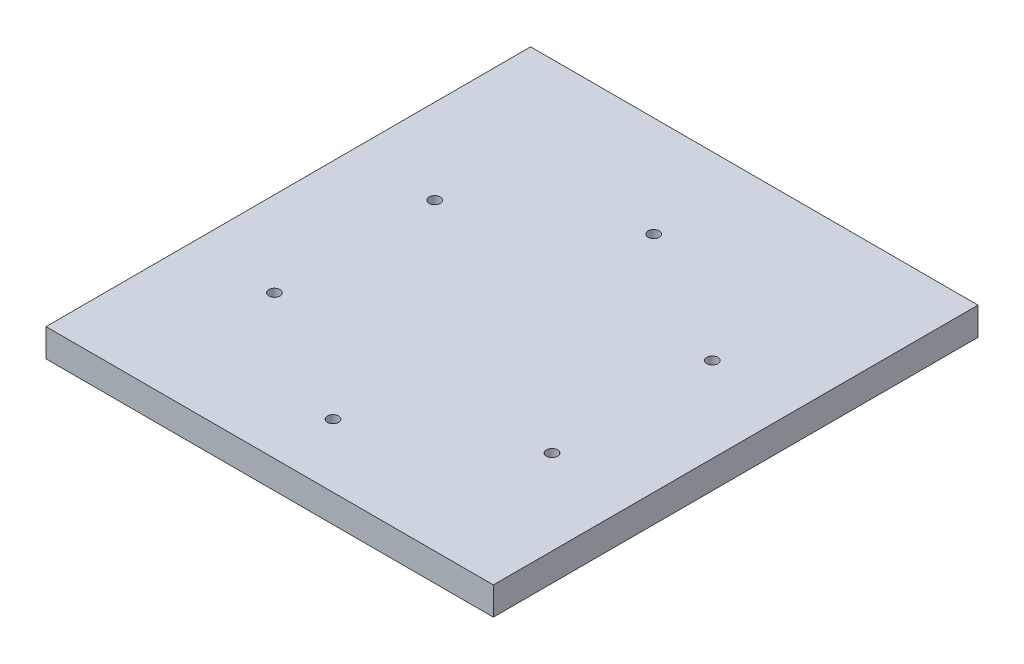
SolidWorks part; units mm, degrees
ref_plane "Alzado" through (0, 0, 0) normal (0, 0, 1) x (1, 0, 0)
ref_plane "Planta" through (0, 0, 0) normal (0, 1, 0) x (1, 0, 0)
ref_plane "Vista lateral" through (0, 0, 0) normal (1, 0, 0) x (0, 0, -1)
sketch "Croquis1" plane through (0, 0, 0) normal (0, 1, 0) x (1, 0, 0)
  line L0 (100, 10) -> (-100, 10) construction
  line L1 (-120, 110) -> (120, 110)
  line L2 (-120, 110) -> (-120, -110)
  line L3 (-120, -110) -> (120, -110)
  line L4 (120, 110) -> (120, -110)
  line L5 (-120, 110) -> (120, -110) construction
  line L6 (-120, -110) -> (120, 110) construction
  line L7 (0, -90) -> (0, 110) construction
  circle A2 centre (0, 96) radius 3
  circle A3 centre (0, -76) radius 3
  circle A4 centre (-74.4782, 53) radius 3
  circle A5 centre (-74.4782, -33) radius 3
  circle A6 centre (74.4782, 53) radius 3
  circle A7 centre (74.4782, -33) radius 3
  point P0 (0, 0)
  dimension "D8" = 0
  dimension "D14" = 86
  dimension "D3" = 220
  dimension "D4" = 240
  dimension "D9" = 86
extrude "Saliente-Extruir1" add sketch "Croquis1" along normal blind 15
sketch "Croquis2" plane through (0, 15, 0) normal (0, 1, 0) x (1, 0, 0)
  line L0 (120, -110) -> (120, 110) construction
  line L1 (-120, 110) -> (120, 110)
  line L2 (-120, 110) -> (-120, 150)
  line L3 (-120, 150) -> (120, 150)
  line L4 (120, 110) -> (120, 150)
extrude "Saliente-Extruir2" add sketch "Croquis2" against normal blind 15
